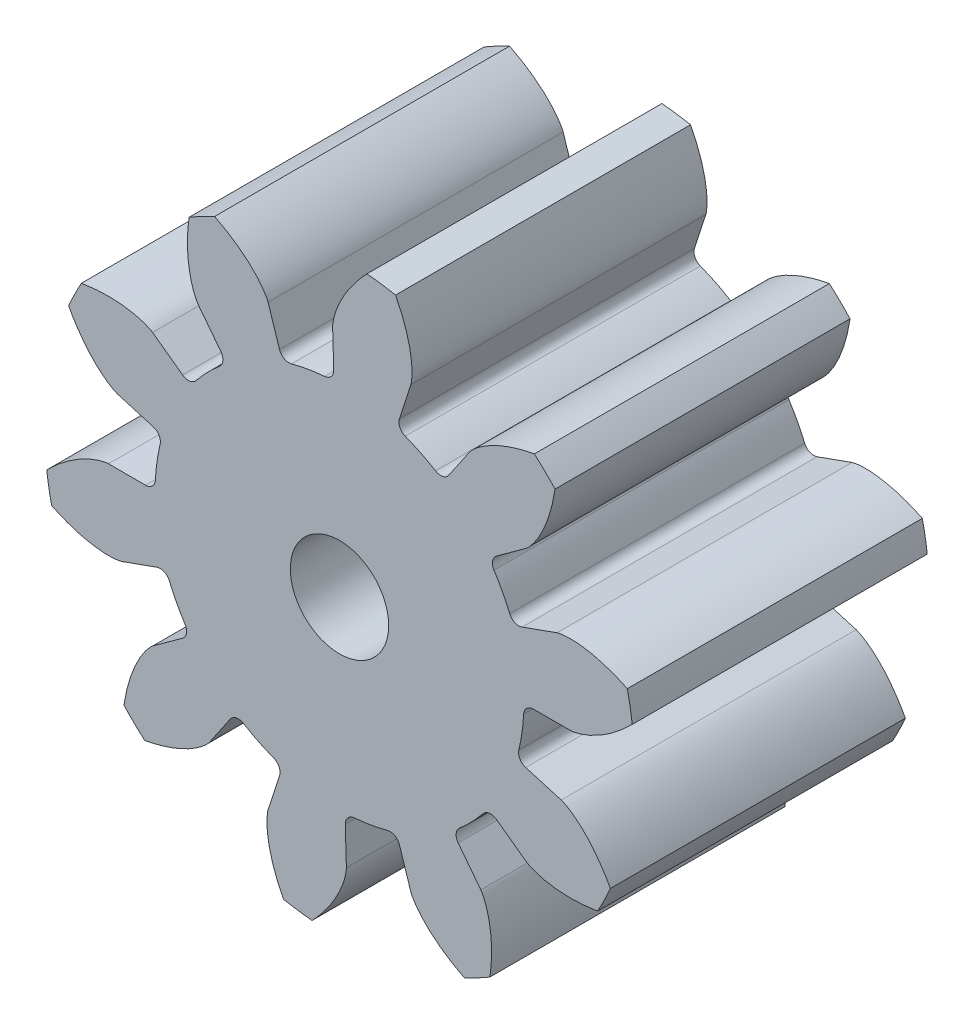
SolidWorks part; units mm, degrees
ref_plane "Front Plane" through (0, 0, 0) normal (0, 0, 1) x (1, 0, 0)
ref_plane "Top Plane" through (0, 0, 0) normal (0, 1, 0) x (1, 0, 0)
ref_plane "Right Plane" through (0, 0, 0) normal (1, 0, 0) x (0, 0, -1)
sketch "Sketch1" plane through (0, 0, 0) normal (0, 0, 1) x (1, 0, 0)
  circle A0 centre (0, 0) radius 3
  circle A1 centre (0, 0) radius 0.5
  dimension "D1" = 6
  dimension "D2" = 1
extrude "Boss-Extrude1" add sketch "Sketch1" along normal blind 3
sketch "Sketch3" plane through (0, 0, 0) normal (0, 0, 1) x (1, 0, 0)
  line L0 (1.875, 0) -> (2.3492, 0)
  line L2 (1.7997, -0.526) -> (2.2549, -0.659)
  line L3 (0, 0) -> (2.9697, -0.4251) construction
  circle A0 centre (0, 0) radius 2.5 construction
  circle A1 centre (0, 0) radius 2.3492 construction
  arc A2 (1.7997, -0.526) -> (1.875, 0) centre (0, 0) ccw
  circle A3 centre (0, 0) radius 3 construction
  spline S0 degree 4 poles (2.3492, 0) (2.3523, 0.0001) (2.3582, 0.0005) (2.3678, 0.0015) (2.3867, 0.0043) (2.4078, 0.0086) (2.4315, 0.0146) (2.4568, 0.0221) (2.4783, 0.0293) (2.4996, 0.0371) (2.5206, 0.0454) (2.5459, 0.0561) (2.5759, 0.07) (2.6106, 0.0875) (2.6494, 0.1089) (2.6883, 0.1324) (2.7261, 0.1568) (2.7636, 0.1831) (2.7993, 0.2095) (2.8357, 0.2385) (2.869, 0.2661) (2.9053, 0.2986) (2.9344, 0.3253) (2.9717, 0.3622) (2.9935, 0.3845) (3.0186, 0.4112) (3.0295, 0.4234) (3.0363, 0.4309) knots 0 0 0 0 0 0.015084 0.028532 0.04661 0.092111 0.119476 0.146842 0.174209 0.201575 0.228941 0.256307 0.307035 0.361767 0.4165 0.471232 0.525964 0.580697 0.635429 0.690161 0.744894 0.799626 0.854358 0.909091 0.954545 1 1 1 1 1 construction
  spline S1 degree 4 poles (2.3492, 0) (2.3523, 0.0001) (2.3582, 0.0005) (2.3678, 0.0015) (2.3867, 0.0043) (2.4078, 0.0086) (2.4315, 0.0146) (2.4568, 0.0221) (2.4783, 0.0293) (2.4996, 0.0371) (2.5206, 0.0454) (2.5459, 0.0561) (2.5759, 0.07) (2.6106, 0.0875) (2.6494, 0.1089) (2.6883, 0.1324) (2.7261, 0.1568) (2.7636, 0.1831) (2.7993, 0.2095) (2.8357, 0.2385) (2.869, 0.2661) (2.9053, 0.2986) (2.9344, 0.3253) (2.9636, 0.3542) (2.9777, 0.3685) (2.9849, 0.3759) knots 0 0 0 0 0 0.015084 0.028532 0.04661 0.092111 0.119476 0.146842 0.174209 0.201575 0.228941 0.256307 0.307035 0.361767 0.4165 0.471232 0.525964 0.580697 0.635429 0.690161 0.744894 0.799626 0.854358 0.909091 0.909091 0.909091 0.909091 0.909091
  spline S2 degree 4 poles (2.2549, -0.659) (2.2579, -0.66) (2.2634, -0.662) (2.2723, -0.6656) (2.2896, -0.6736) (2.3087, -0.6837) (2.3298, -0.6961) (2.352, -0.7105) (2.3706, -0.7234) (2.3888, -0.7368) (2.4066, -0.7507) (2.4279, -0.7681) (2.4529, -0.7898) (2.4813, -0.8163) (2.5125, -0.8478) (2.5433, -0.8812) (2.5726, -0.9153) (2.6012, -0.951) (2.6282, -0.9864) (2.655, -1.0245) (2.6791, -1.0602) (2.7049, -1.1016) (2.7253, -1.1354) (2.7508, -1.1813) (2.7654, -1.2089) (2.782, -1.2415) (2.7891, -1.2563) (2.7935, -1.2654) knots 0 0 0 0 0 0.015084 0.028532 0.04661 0.092111 0.119476 0.146842 0.174209 0.201575 0.228941 0.256307 0.307035 0.361767 0.4165 0.471232 0.525964 0.580697 0.635429 0.690161 0.744894 0.799626 0.854358 0.909091 0.954545 1 1 1 1 1 construction
  spline S3 degree 4 poles (2.2549, -0.659) (2.2579, -0.66) (2.2634, -0.662) (2.2723, -0.6656) (2.2896, -0.6736) (2.3087, -0.6837) (2.3298, -0.6961) (2.352, -0.7105) (2.3706, -0.7234) (2.3888, -0.7368) (2.4066, -0.7507) (2.4279, -0.7681) (2.4529, -0.7898) (2.4813, -0.8163) (2.5125, -0.8478) (2.5433, -0.8812) (2.5726, -0.9153) (2.6012, -0.951) (2.6282, -0.9864) (2.655, -1.0245) (2.6791, -1.0602) (2.7049, -1.1016) (2.7253, -1.1354) (2.7453, -1.1714) (2.7548, -1.189) (2.7596, -1.1981) knots 0 0 0 0 0 0.015084 0.028532 0.04661 0.092111 0.119476 0.146842 0.174209 0.201575 0.228941 0.256307 0.307035 0.361767 0.4165 0.471232 0.525964 0.580697 0.635429 0.690161 0.744894 0.799626 0.854358 0.909091 0.909091 0.909091 0.909091 0.909091
  point P5 (1.875, 0)
  point P11 (1.7997, -0.526)
  dimension "D1" = 5
  dimension "D2" = 4.6985
  dimension "D3" = 3.75
  dimension "D4" = 8.146
  dimension "D5" = 8.146
extrude "Cut-Extrude1" cut sketch "Sketch3" against normal through all and the other way through all
fillet "Fillet1" radius 0.1 1 edges at (1.7997, -0.526, 1.5)
fillet "Fillet2" radius 0.1 1 edges at (1.875, 0, 1.5)
pattern_circular "CirPattern14" count 10 over 360 about axis through (0, 0, 3) along (0, 0, -1) of "Cut-Extrude1", "Fillet1", "Fillet2"
equation "\"P\"= 2'Diametral Pitch"
equation "\"N\"= 10'Number of teeth"
equation "\"phi\"= 20deg'pressure angle"
equation "\"a\"= 1 / \"P\"'addendum"
equation "\"b\"= 1.25 / \"P\"'dedendum"
equation "\"c\"= \"b\" - \"a\"'clearance"
equation "\"dp\"= \"N\" / \"P\"'pitch circle diameter"
equation "\"db\"= \"dp\" * cos ( \"phi\" )'base circle diameter"
equation "\"D1@Sketch1\"= \"dp\" + 2 * \"a\"'Addendum circle diameter"
equation "\"D1@Sketch3\"= \"dp\"'pitch circle"
equation "\"D2@Sketch3\"= \"db\" 'base circle"
equation "\"D3@Sketch3\" = \"dp\" - 2 * \"b\"'dedendum circle"
equation "\"alpha\"= sqr ( \"dp\" ^ 2 - \"db\" ^ 2 ) / \"db\" * 180 / pi - \"phi\"'alpha (deg)"
equation "\"beta\"= ( 360 / ( 4 * \"N\" ) - \"alpha\" ) * 2"
equation "\"D4@Sketch3\"= 360 / ( 4 * \"N\" ) - \"alpha\""
equation "\"D5@Sketch3\"= 360 / ( 4 * \"N\" ) - \"alpha\""
